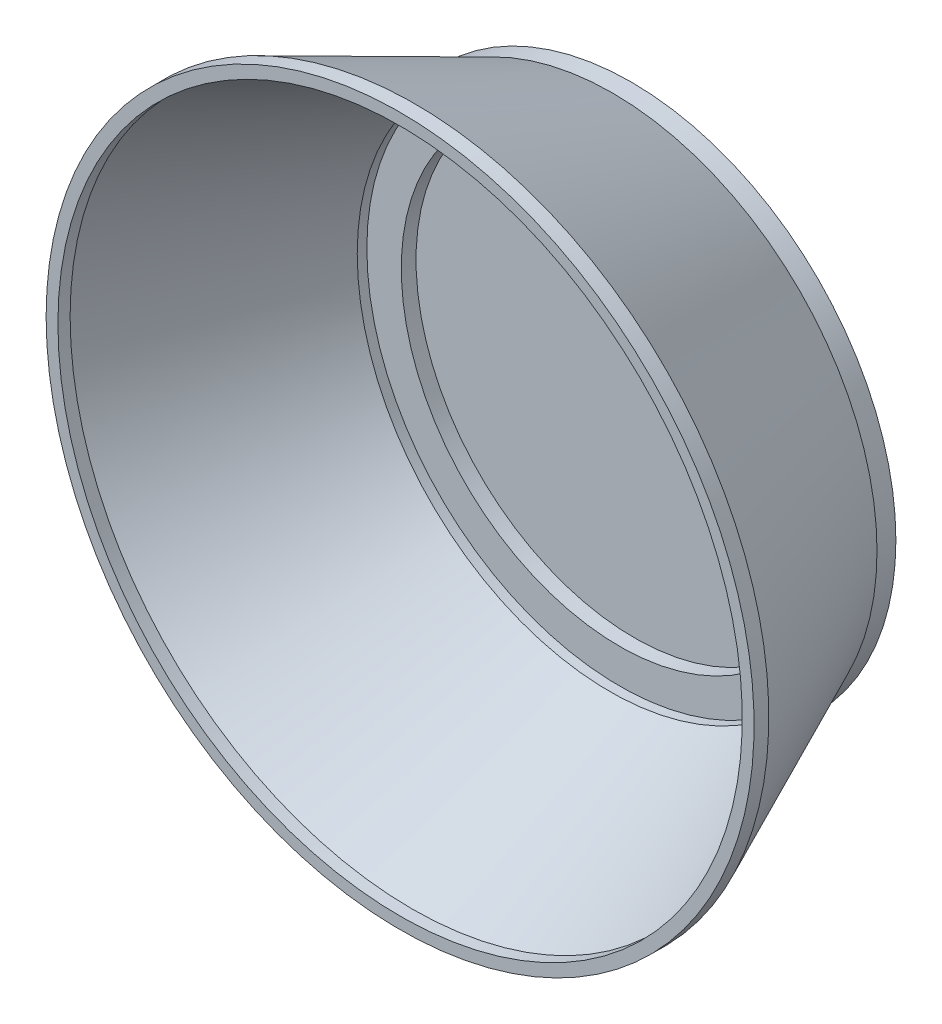
SolidWorks part; units mm, degrees
ref_plane "Front Plane" through (0, 0, 0) normal (1, 0, 0) x (0, 1, 0)
ref_plane "Top Plane" through (0, 0, 0) normal (0, 0, 1) x (0, 1, 0)
ref_plane "Right Plane" through (0, 0, 0) normal (0, 1, 0) x (-1, 0, 0)
sketch "Sketch1" plane through (0, 0, 0) normal (0, 1, 0) x (-1, 0, 0)
  line L0 (0, 0) -> (0, 26.4795)
  line L1 (0, 0) -> (-24.765, 0)
  line L2 (-24.765, 0) -> (-24.765, 1.5875)
  line L3 (-24.765, 1.5875) -> (-28.4703, 1.5875)
  line L4 (-28.4703, 1.5875) -> (-28.4703, 3.6195)
  line L5 (-28.4703, 3.6195) -> (-38.1, 24.892)
  line L6 (-38.1, 24.892) -> (-38.1, 26.4795)
  line L7 (-38.1, 26.4795) -> (0, 26.4795)
  dimension "D1" = 24.892
  dimension "D2" = 1.5875
  dimension "D3" = 24.765
  dimension "D4" = 28.4703
  dimension "D5" = 2.032
  dimension "D6" = 1.5875
  dimension "D7" = 38.1
revolve "Revolve1" add sketch "Sketch1" angle 360 about L0
shell "Shell1" thickness 1.27
